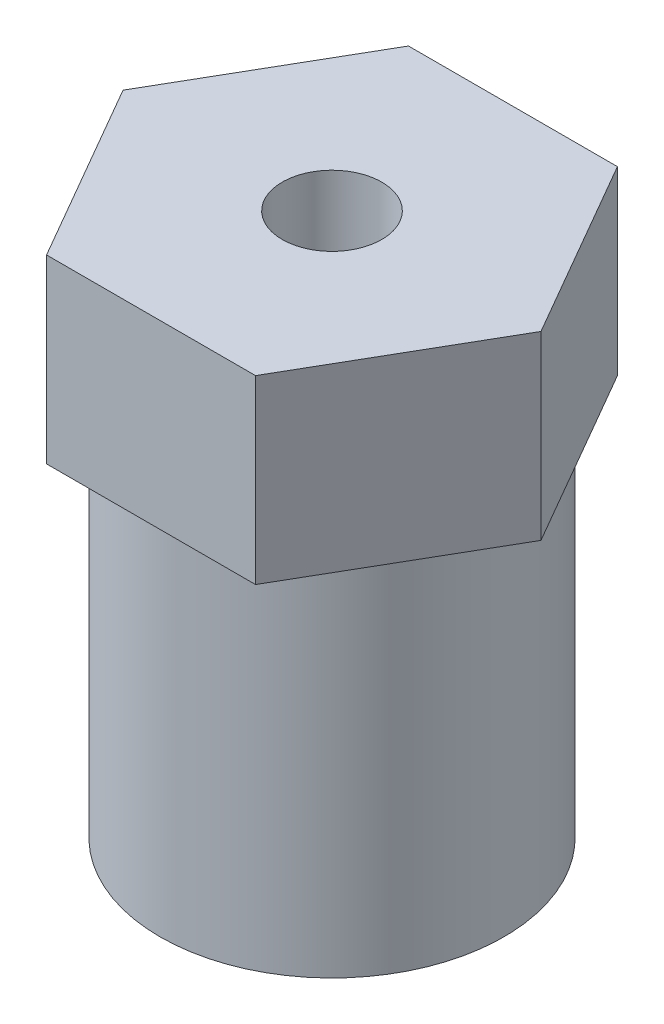
SolidWorks part; units mm, degrees
ref_plane "Front Plane" through (0, 0, 0) normal (0, 0, 1) x (1, 0, 0)
ref_plane "Top Plane" through (0, 0, 0) normal (0, 1, 0) x (1, 0, 0)
ref_plane "Right Plane" through (0, 0, 0) normal (1, 0, 0) x (0, 0, -1)
sketch "Sketch1" plane through (0, 0, 0) normal (0, 1, 0) x (1, 0, 0)
  circle A0 centre (0, 0) radius 5.7
  circle A1 centre (0, 0) radius 2.55
  dimension "D1" = 11.4
  dimension "D2" = 5.1
extrude "Boss-Extrude1" add sketch "Sketch1" along normal blind 12
sketch "Sketch2" plane through (0, 12, 0) normal (0, 1, 0) x (1, 0, 0)
  line L1 (6.9282, 0) -> (3.4641, 6)
  line L2 (3.4641, 6) -> (-3.4641, 6)
  line L3 (-3.4641, 6) -> (-6.9282, 0)
  line L4 (-6.9282, 0) -> (-3.4641, -6)
  line L5 (-3.4641, -6) -> (3.4641, -6)
  line L6 (3.4641, -6) -> (6.9282, 0)
  circle A0 centre (0, 0) radius 6 construction
  circle A1 centre (0, 0) radius 1.65
  dimension "D1" = 12
extrude "Boss-Extrude2" add sketch "Sketch2" along normal blind 6
